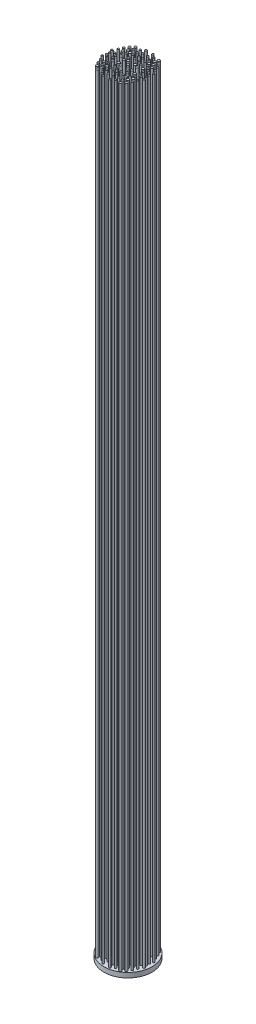
SolidWorks part; units mm, degrees
ref_plane "Front Plane" through (0, 0, 0) normal (0, 0, 1) x (1, 0, 0)
ref_plane "Top Plane" through (0, 0, 0) normal (0, 1, 0) x (1, 0, 0)
ref_plane "Right Plane" through (0, 0, 0) normal (1, 0, 0) x (0, 0, -1)
sketch "Sketch1" plane through (0, 0, 0) normal (0, 1, 0) x (1, 0, 0)
  circle A0 centre (0, 0) radius 6.35
  dimension "D1" = 12.7
extrude "Boss-Extrude1" add sketch "Sketch1" along normal blind 1.27
sketch "Sketch3" plane through (0, 1.27, 0) normal (0, 1, 0) x (1, 0, 0)
  line L0 (0, 6.35) -> (0, -6.35) construction
  line L1 (-6.35, 0) -> (6.35, 0) construction
  circle A0 centre (0, 0) radius 0.3175
  circle A1 centre (-2.8089, 4.2606) radius 0.3175
  circle A2 centre (0, 0) radius 6.35 construction
  circle A3 centre (-2.5126, 3.0582) radius 0.3175
  circle A4 centre (-3.3491, 3.3719) radius 0.3175
  circle A5 centre (-3.8544, 2.4832) radius 0.3175
  circle A6 centre (-4.4643, 3.3719) radius 0.2419
  circle A7 centre (-4.8726, 2.3438) radius 0.2419
  circle A8 centre (-5.4925, 1.2634) radius 0.2419
  circle A9 centre (-4.4946, 0.9878) radius 0.2419
  circle A10 centre (-2.879, 1.1065) radius 0.3175
  circle A11 centre (-3.6392, 1.7687) radius 0.2419
  circle A12 centre (-1.6413, 1.7687) radius 0.2419
  circle A13 centre (-1.6413, 4.0341) radius 0.2419
  circle A14 centre (-1.7633, 5.0448) radius 0.2419
  circle A15 centre (-0.9094, 5.6721) radius 0.2419
  circle A16 centre (-0.635, 4.5743) radius 0.2419
  circle A17 centre (-0.508, 3.4246) radius 0.2419
  circle A18 centre (-0.6096, 2.3438) radius 0.2419
  circle A19 centre (-2.879, 2.3438) radius 0.2419
  circle A20 centre (-0.9094, 0.9878) radius 0.3175
  circle A21 centre (-1.7633, 0.7135) radius 0.3175
  circle A22 centre (-3.6392, 0.3831) radius 0.2419
  circle A23 centre (-5.2169, 0.3831) radius 0.2419
  circle A24 centre (-1.6413, 2.9188) radius 0.2419
  circle A25 centre (-3.0528, 5.0448) radius 0.3175
  circle A26 centre (-3.8544, 4.2606) radius 0.3175
  circle A27 centre (-3.8544, -4.2606) radius 0.3175
  circle A28 centre (-3.0528, -5.0448) radius 0.3175
  circle A29 centre (-1.6413, -2.9188) radius 0.2419
  circle A30 centre (-5.2169, -0.3831) radius 0.2419
  circle A31 centre (-3.6392, -0.3831) radius 0.2419
  circle A32 centre (-1.7633, -0.7135) radius 0.3175
  circle A33 centre (-0.9094, -0.9878) radius 0.3175
  circle A34 centre (-2.879, -2.3438) radius 0.2419
  circle A35 centre (-0.6096, -2.3438) radius 0.2419
  circle A36 centre (-0.508, -3.4246) radius 0.2419
  circle A37 centre (-0.635, -4.5743) radius 0.2419
  circle A38 centre (-0.9094, -5.6721) radius 0.2419
  circle A39 centre (-1.7633, -5.0448) radius 0.2419
  circle A40 centre (-1.6413, -4.0341) radius 0.2419
  circle A41 centre (-1.6413, -1.7687) radius 0.2419
  circle A42 centre (-3.6392, -1.7687) radius 0.2419
  circle A43 centre (-2.879, -1.1065) radius 0.3175
  circle A44 centre (-4.4946, -0.9878) radius 0.2419
  circle A45 centre (-5.4925, -1.2634) radius 0.2419
  circle A46 centre (-4.8726, -2.3438) radius 0.2419
  circle A47 centre (-4.4643, -3.3719) radius 0.2419
  circle A48 centre (-3.8544, -2.4832) radius 0.3175
  circle A49 centre (-3.3491, -3.3719) radius 0.3175
  circle A50 centre (-2.5126, -3.0582) radius 0.3175
  circle A51 centre (-2.8089, -4.2606) radius 0.3175
  circle A52 centre (-2.8089, 4.2606) radius 0.3175
  circle A53 centre (-2.5126, 3.0582) radius 0.3175
  circle A54 centre (-3.3491, 3.3719) radius 0.3175
  circle A55 centre (-3.8544, 2.4832) radius 0.3175
  circle A56 centre (-4.4643, 3.3719) radius 0.2419
  circle A57 centre (-4.8726, 2.3438) radius 0.2419
  circle A58 centre (-5.4925, 1.2634) radius 0.2419
  circle A59 centre (-4.4946, 0.9878) radius 0.2419
  circle A60 centre (-2.879, 1.1065) radius 0.3175
  circle A61 centre (-3.6392, 1.7687) radius 0.2419
  circle A62 centre (-1.6413, 1.7687) radius 0.2419
  circle A63 centre (-1.6413, 4.0341) radius 0.2419
  circle A64 centre (-1.7633, 5.0448) radius 0.2419
  circle A65 centre (-0.9094, 5.6721) radius 0.2419
  circle A66 centre (-0.635, 4.5743) radius 0.2419
  circle A67 centre (-0.508, 3.4246) radius 0.2419
  circle A68 centre (-0.6096, 2.3438) radius 0.2419
  circle A69 centre (-2.879, 2.3438) radius 0.2419
  circle A70 centre (-0.9094, 0.9878) radius 0.3175
  circle A71 centre (-1.7633, 0.7135) radius 0.3175
  circle A72 centre (-3.6392, 0.3831) radius 0.2419
  circle A73 centre (-5.2169, 0.3831) radius 0.2419
  circle A74 centre (-1.6413, 2.9188) radius 0.2419
  circle A75 centre (-3.0528, 5.0448) radius 0.3175
  circle A76 centre (-3.8544, 4.2606) radius 0.3175
  circle A77 centre (-3.8544, -4.2606) radius 0.3175
  circle A78 centre (-3.0528, -5.0448) radius 0.3175
  circle A79 centre (-1.6413, -2.9188) radius 0.2419
  circle A80 centre (-5.2169, -0.3831) radius 0.2419
  circle A81 centre (-3.6392, -0.3831) radius 0.2419
  circle A82 centre (-1.7633, -0.7135) radius 0.3175
  circle A83 centre (-0.9094, -0.9878) radius 0.3175
  circle A84 centre (-2.879, -2.3438) radius 0.2419
  circle A85 centre (-0.6096, -2.3438) radius 0.2419
  circle A86 centre (-0.508, -3.4246) radius 0.2419
  circle A87 centre (-0.635, -4.5743) radius 0.2419
  circle A88 centre (-0.9094, -5.6721) radius 0.2419
  circle A89 centre (-1.7633, -5.0448) radius 0.2419
  circle A90 centre (-1.6413, -4.0341) radius 0.2419
  circle A91 centre (-1.6413, -1.7687) radius 0.2419
  circle A92 centre (-3.6392, -1.7687) radius 0.2419
  circle A93 centre (-2.879, -1.1065) radius 0.3175
  circle A94 centre (-4.4946, -0.9878) radius 0.2419
  circle A95 centre (-5.4925, -1.2634) radius 0.2419
  circle A96 centre (-4.8726, -2.3438) radius 0.2419
  circle A97 centre (-4.4643, -3.3719) radius 0.2419
  circle A98 centre (-3.8544, -2.4832) radius 0.3175
  circle A99 centre (-3.3491, -3.3719) radius 0.3175
  circle A100 centre (-2.5126, -3.0582) radius 0.3175
  circle A101 centre (-2.8089, -4.2606) radius 0.3175
  circle A102 centre (2.8089, -4.2606) radius 0.3175
  circle A103 centre (2.5126, -3.0582) radius 0.3175
  circle A104 centre (3.3491, -3.3719) radius 0.3175
  circle A105 centre (3.8544, -2.4832) radius 0.3175
  circle A106 centre (4.4643, -3.3719) radius 0.2419
  circle A107 centre (4.8726, -2.3438) radius 0.2419
  circle A108 centre (5.4925, -1.2634) radius 0.2419
  circle A109 centre (4.4946, -0.9878) radius 0.2419
  circle A110 centre (2.879, -1.1065) radius 0.3175
  circle A111 centre (3.6392, -1.7687) radius 0.2419
  circle A112 centre (1.6413, -1.7687) radius 0.2419
  circle A113 centre (1.6413, -4.0341) radius 0.2419
  circle A114 centre (1.7633, -5.0448) radius 0.2419
  circle A115 centre (0.9094, -5.6721) radius 0.2419
  circle A116 centre (0.635, -4.5743) radius 0.2419
  circle A117 centre (0.508, -3.4246) radius 0.2419
  circle A118 centre (0.6096, -2.3438) radius 0.2419
  circle A119 centre (2.879, -2.3438) radius 0.2419
  circle A120 centre (0.9094, -0.9878) radius 0.3175
  circle A121 centre (1.7633, -0.7135) radius 0.3175
  circle A122 centre (3.6392, -0.3831) radius 0.2419
  circle A123 centre (5.2169, -0.3831) radius 0.2419
  circle A124 centre (1.6413, -2.9188) radius 0.2419
  circle A125 centre (3.0528, -5.0448) radius 0.3175
  circle A126 centre (3.8544, -4.2606) radius 0.3175
  circle A127 centre (3.8544, 4.2606) radius 0.3175
  circle A128 centre (3.0528, 5.0448) radius 0.3175
  circle A129 centre (1.6413, 2.9188) radius 0.2419
  circle A130 centre (5.2169, 0.3831) radius 0.2419
  circle A131 centre (3.6392, 0.3831) radius 0.2419
  circle A132 centre (1.7633, 0.7135) radius 0.3175
  circle A133 centre (0.9094, 0.9878) radius 0.3175
  circle A134 centre (2.879, 2.3438) radius 0.2419
  circle A135 centre (0.6096, 2.3438) radius 0.2419
  circle A136 centre (0.508, 3.4246) radius 0.2419
  circle A137 centre (0.635, 4.5743) radius 0.2419
  circle A138 centre (0.9094, 5.6721) radius 0.2419
  circle A139 centre (1.7633, 5.0448) radius 0.2419
  circle A140 centre (1.6413, 4.0341) radius 0.2419
  circle A141 centre (1.6413, 1.7687) radius 0.2419
  circle A142 centre (3.6392, 1.7687) radius 0.2419
  circle A143 centre (2.879, 1.1065) radius 0.3175
  circle A144 centre (4.4946, 0.9878) radius 0.2419
  circle A145 centre (5.4925, 1.2634) radius 0.2419
  circle A146 centre (4.8726, 2.3438) radius 0.2419
  circle A147 centre (4.4643, 3.3719) radius 0.2419
  circle A148 centre (3.8544, 2.4832) radius 0.3175
  circle A149 centre (3.3491, 3.3719) radius 0.3175
  circle A150 centre (2.5126, 3.0582) radius 0.3175
  circle A151 centre (2.8089, 4.2606) radius 0.3175
  circle A152 centre (2.8089, -4.2606) radius 0.3175
  circle A153 centre (2.5126, -3.0582) radius 0.3175
  circle A154 centre (3.3491, -3.3719) radius 0.3175
  circle A155 centre (3.8544, -2.4832) radius 0.3175
  circle A156 centre (4.4643, -3.3719) radius 0.2419
  circle A157 centre (4.8726, -2.3438) radius 0.2419
  circle A158 centre (5.4925, -1.2634) radius 0.2419
  circle A159 centre (4.4946, -0.9878) radius 0.2419
  circle A160 centre (2.879, -1.1065) radius 0.3175
  circle A161 centre (3.6392, -1.7687) radius 0.2419
  circle A162 centre (1.6413, -1.7687) radius 0.2419
  circle A163 centre (1.6413, -4.0341) radius 0.2419
  circle A164 centre (1.7633, -5.0448) radius 0.2419
  circle A165 centre (0.9094, -5.6721) radius 0.2419
  circle A166 centre (0.635, -4.5743) radius 0.2419
  circle A167 centre (0.508, -3.4246) radius 0.2419
  circle A168 centre (0.6096, -2.3438) radius 0.2419
  circle A169 centre (2.879, -2.3438) radius 0.2419
  circle A170 centre (0.9094, -0.9878) radius 0.3175
  circle A171 centre (1.7633, -0.7135) radius 0.3175
  circle A172 centre (3.6392, -0.3831) radius 0.2419
  circle A173 centre (5.2169, -0.3831) radius 0.2419
  circle A174 centre (1.6413, -2.9188) radius 0.2419
  circle A175 centre (3.0528, -5.0448) radius 0.3175
  circle A176 centre (3.8544, -4.2606) radius 0.3175
  circle A177 centre (3.8544, 4.2606) radius 0.3175
  circle A178 centre (3.0528, 5.0448) radius 0.3175
  circle A179 centre (1.6413, 2.9188) radius 0.2419
  circle A180 centre (5.2169, 0.3831) radius 0.2419
  circle A181 centre (3.6392, 0.3831) radius 0.2419
  circle A182 centre (1.7633, 0.7135) radius 0.3175
  circle A183 centre (0.9094, 0.9878) radius 0.3175
  circle A184 centre (2.879, 2.3438) radius 0.2419
  circle A185 centre (0.6096, 2.3438) radius 0.2419
  circle A186 centre (0.508, 3.4246) radius 0.2419
  circle A187 centre (0.635, 4.5743) radius 0.2419
  circle A188 centre (0.9094, 5.6721) radius 0.2419
  circle A189 centre (1.7633, 5.0448) radius 0.2419
  circle A190 centre (1.6413, 4.0341) radius 0.2419
  circle A191 centre (1.6413, 1.7687) radius 0.2419
  circle A192 centre (3.6392, 1.7687) radius 0.2419
  circle A193 centre (2.879, 1.1065) radius 0.3175
  circle A194 centre (4.4946, 0.9878) radius 0.2419
  circle A195 centre (5.4925, 1.2634) radius 0.2419
  circle A196 centre (4.8726, 2.3438) radius 0.2419
  circle A197 centre (4.4643, 3.3719) radius 0.2419
  circle A198 centre (3.8544, 2.4832) radius 0.3175
  circle A199 centre (3.3491, 3.3719) radius 0.3175
  circle A200 centre (2.5126, 3.0582) radius 0.3175
  circle A201 centre (2.8089, 4.2606) radius 0.3175
  dimension "D1" = 0.635
  dimension "D2" = 0.508
  dimension "D3" = 0.635
  dimension "D4" = 0.6096
extrude "Boss-Extrude2" add sketch "Sketch3" along normal blind 203.2
